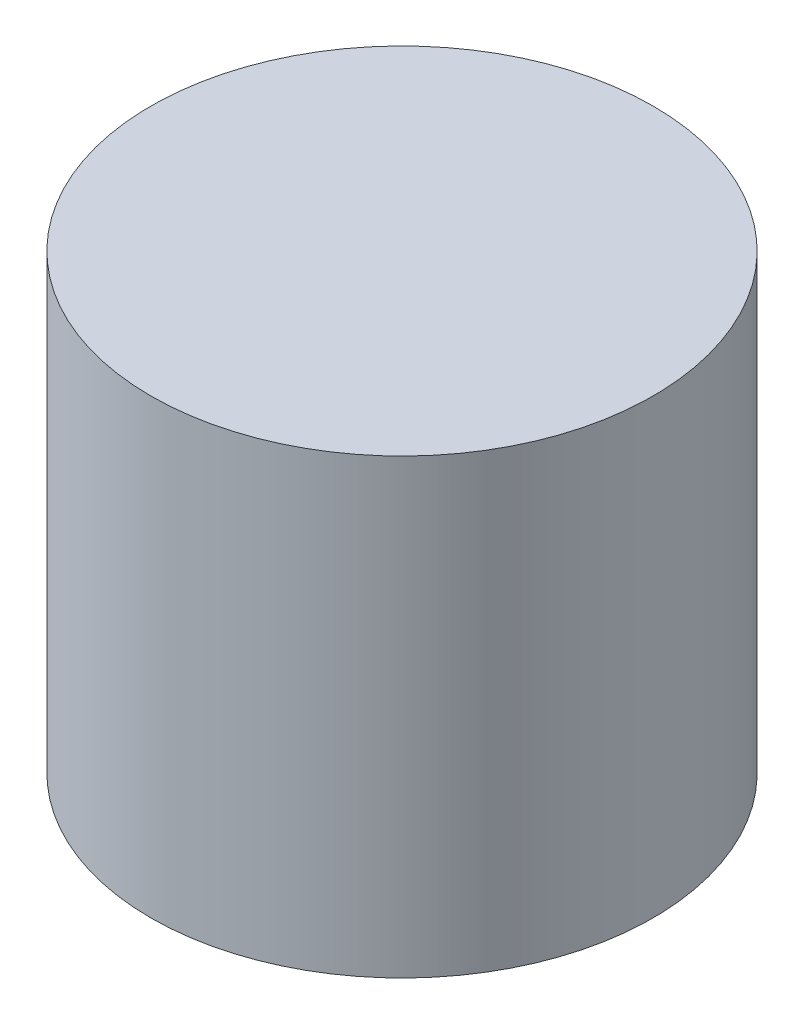
SolidWorks part; units mm, degrees
ref_plane "Plano frontal" through (0, 0, 0) normal (0, 0, 1) x (1, 0, 0)
ref_plane "Plano superior" through (0, 0, 0) normal (0, 1, 0) x (1, 0, 0)
ref_plane "Plano direito" through (0, 0, 0) normal (1, 0, 0) x (0, 0, -1)
sketch "Esboço1" plane through (0, 0, 0) normal (0, 0, 1) x (1, 0, 0)
  line L0 (0, 0) -> (0, 36) construction
  line L1 (0, 0) -> (20, 0)
  line L2 (20, 0) -> (20, 36)
  line L3 (20, 36) -> (0, 36)
  line L4 (0, 0) -> (0, 36)
  point P3 (0, 19.0336)
  point P8 (0, 73.1648)
  point P9 (0, 29.7104)
  point P10 (0, 36)
  point P11 (0, 0)
  dimension "D1" = 20
  dimension "D2" = 36
revolve "Revolução1" add sketch "Esboço1" angle 360 about L0
